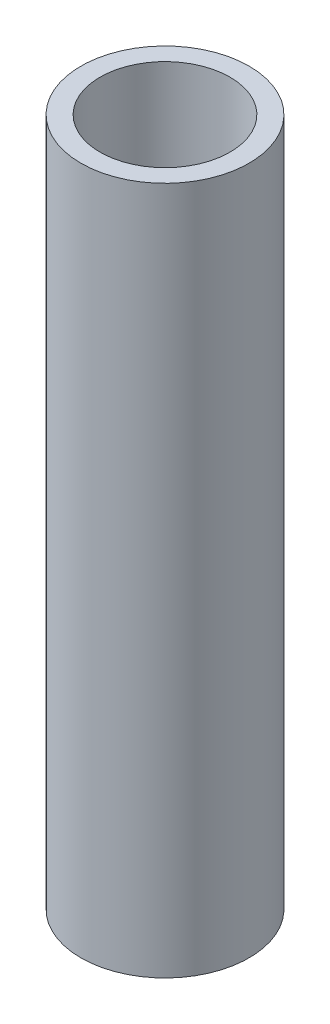
SolidWorks part; units mm, degrees
material "PVC 0.007 Plasticized"
ref_plane "Front Plane" through (0, 0, 0) normal (0, 0, 1) x (1, 0, 0)
ref_plane "Top Plane" through (0, 0, 0) normal (0, 1, 0) x (1, 0, 0)
ref_plane "Right Plane" through (0, 0, 0) normal (1, 0, 0) x (0, 0, -1)
sketch "Sketch1" plane through (0, 0, 0) normal (0, 1, 0) x (1, 0, 0)
  circle A0 centre (0, 0) radius 11
  circle A1 centre (0, 0) radius 8.5
extrude "Boss-Extrude1" add sketch "Sketch1" along normal blind 90
